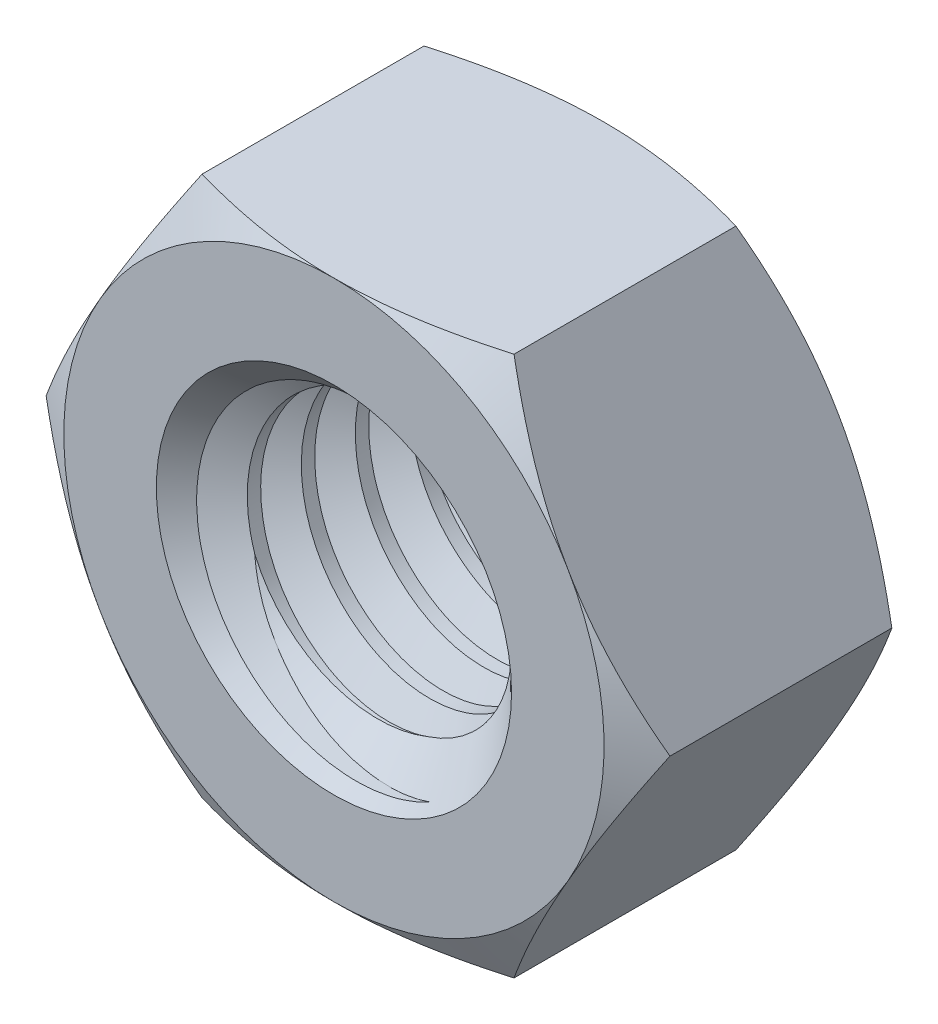
SolidWorks part; units mm, degrees
ref_plane "Front" through (0, 0, 0) normal (0, 0, 1) x (1, 0, 0)
ref_plane "Top" through (0, 0, 0) normal (0, 1, 0) x (1, 0, 0)
ref_plane "Right" through (0, 0, 0) normal (1, 0, 0) x (0, 0, -1)
sketch "Çizim1" plane through (0, 0, 0) normal (0, 0, 1) x (1, 0, 0)
  line L1 (4.6188, 0) -> (2.3094, 4)
  line L2 (2.3094, 4) -> (-2.3094, 4)
  line L3 (-2.3094, 4) -> (-4.6188, 0)
  line L4 (-4.6188, 0) -> (-2.3094, -4)
  line L5 (-2.3094, -4) -> (2.3094, -4)
  line L6 (2.3094, -4) -> (4.6188, 0)
  circle A0 centre (0, 0) radius 4 construction
  dimension "D1" = 8
extrude "Yükseklik-Ekstrüzyon1" add sketch "Çizim1" along normal blind 4
sketch "Çizim2" plane through (0, 0, 4) normal (0, 0, 1) x (1, 0, 0)
  circle A0 centre (0, 0) radius 4
extrude "Kes-Ekstrüzyon1" cut sketch "Çizim2" against normal blind 4 draft 60 flip side to cut
sketch "Çizim3" plane through (0, 0, 0) normal (0, 0, -1) x (-1, 0, 0)
  circle A0 centre (0, 0) radius 4
extrude "Kes-Ekstrüzyon2" cut sketch "Çizim3" against normal blind 4 draft 60 flip side to cut
sketch "Çizim4" plane through (0, 0, 4) normal (0, 0, 1) x (1, 0, 0)
  circle A0 centre (0, 0) radius 1.98
  dimension "D1" = 3.96
extrude "Kes-Ekstrüzyon3" cut sketch "Çizim4" against normal blind 4
chamfer "Pah1" distance 0.65 angle 45 2 edges at (1.98, 0, 0) (1.98, 0, 4)
sketch "Çizim5" plane through (0, 0, 0) normal (0, 0, -1) x (-1, 0, 0)
  circle A0 centre (0, 0) radius 1.98
curve "Helis/Spiral1" pitch 0.8 height 5 turns 6.25
ref_plane "Düzlem1" through (0, 1.98, 5) normal (-0.9979, 0, 0.0642) x (0.0642, 0, 0.9979)
sketch "Çizim6" plane through (0, 1.98, 5) normal (-0.9979, 0, 0.0642) x (0.0642, 0, 0.9979)
  line L1 (0, 0.52) -> (-0.3833, -0.1439)
  line L3 (0.3833, -0.1439) -> (0, 0.52)
  line L4 (0.3833, -0.1439) -> (-0.3833, -0.1439)
  line L5 (0, -0.26) -> (0.4503, -0.26) [skipped]
  circle A0 centre (0, 0) radius 0.26 construction
  dimension "D1" = 0.52
sweep "Kes-Süpür1" cut profiles "Çizim6" path "Helis/Spiral1"
